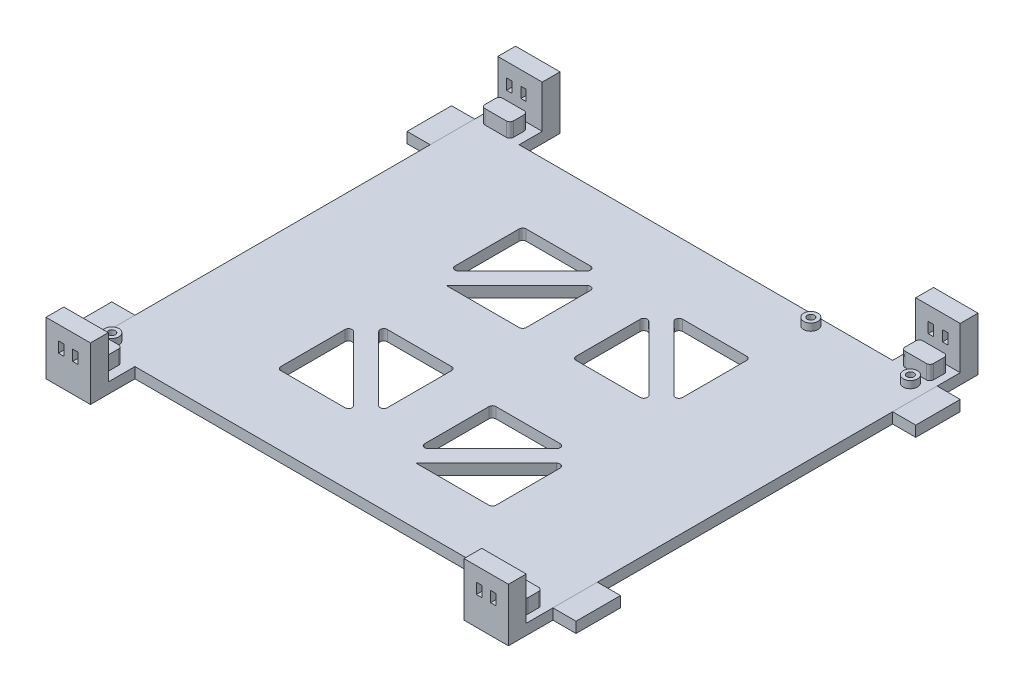
SolidWorks part; units mm, degrees
ref_plane "Front Plane" through (0, 0, 0) normal (0, 0, 1) x (1, 0, 0)
ref_plane "Top Plane" through (0, 0, 0) normal (0, 1, 0) x (1, 0, 0)
ref_plane "Right Plane" through (0, 0, 0) normal (1, 0, 0) x (0, 0, -1)
sketch "Sketch1" plane through (0, 0, 0) normal (0, 1, 0) x (1, 0, 0)
  line L0 (3, 0) -> (3, 3) construction
  line L1 (0, 0) -> (130, 0)
  line L2 (0, 0) -> (0, 108)
  line L3 (0, 108) -> (130, 108)
  line L4 (130, 0) -> (130, 108)
  line L5 (125.5, 108) -> (125.5, 105) construction
  line L6 (125.5, 105) -> (97.5, 105) construction
  line L8 (0, 0) -> (12.5, 0)
  line L9 (0, 0) -> (0, -12.5)
  line L10 (0, -12.5) -> (12.5, -12.5)
  line L11 (12.5, 0) -> (12.5, -12.5)
  line L12 (130, 0) -> (117.5, 0)
  line L13 (130, 0) -> (130, -12.5)
  line L14 (130, -12.5) -> (117.5, -12.5)
  line L15 (117.5, 0) -> (117.5, -12.5)
  line L16 (0, 108) -> (12.5, 108)
  line L17 (0, 108) -> (0, 119.5)
  line L18 (0, 119.5) -> (12.5, 119.5)
  line L19 (12.5, 108) -> (12.5, 119.5)
  line L20 (130, 108) -> (117.5, 108)
  line L21 (130, 108) -> (130, 119.5)
  line L22 (130, 119.5) -> (117.5, 119.5)
  line L23 (117.5, 108) -> (117.5, 119.5)
  circle A0 centre (3, 3) radius 1
  circle A1 centre (125.5, 105) radius 1
  circle A2 centre (97.5, 105) radius 1
  circle A3 centre (3, 3) radius 2
  circle A4 centre (97.5, 105) radius 2
  circle A5 centre (125.5, 105) radius 2
  point P7 (3, 1.5)
  point P11 (125.5, 106.5)
  dimension "D5" = 2
  dimension "D8" = 2
  dimension "D10" = 2
  dimension "D11" = 4
  dimension "D12" = 4
  dimension "D13" = 4
  dimension "D1" = 130
  dimension "D2" = 108
  dimension "D3" = 3
  dimension "D4" = 3
  dimension "D6" = 3
  dimension "D7" = 4.5
  dimension "D9" = 28
  dimension "D14" = 12.5
  dimension "D15" = 12.5
  dimension "D16" = 12.5
  dimension "D17" = 12.5
  dimension "D18" = 11.5
  dimension "D19" = 12.5
  dimension "D20" = 11.5
  dimension "D21" = 12.5
extrude "Boss-Extrude2" add sketch "Sketch1" along normal blind 3 contours L1 L4 L3 L2 A5 A4 A3 | A3 A0 | A5 A1 | A4 A2 | L3 L19 L18 L17 | L23 L3 L21 L22 | L1 L15 L14 L13 | L11 L1 L9 L10
sketch "Sketch3" plane through (0, 3, 0) normal (0, 1, 0) x (1, 0, 0)
  circle A0 centre (97.5, 105) radius 2
  circle A1 centre (125.5, 105) radius 2
  circle A2 centre (3, 3) radius 2
  circle A3 centre (3, 3) radius 1
  circle A4 centre (97.5, 105) radius 1
  circle A5 centre (125.5, 105) radius 1
  circle M7 centre (3, 3) radius 1
  circle M8 centre (97.5, 105) radius 1
  circle M9 centre (125.5, 105) radius 1
  dimension "D1" = 4
  dimension "D2" = 4
  dimension "D3" = 4
extrude "Boss-Extrude3" add sketch "Sketch3" along normal blind 2 contours A2 M7 | A0 M8 | A1 M9
sketch "Sketch5" plane through (0, 3, 0) normal (0, 1, 0) x (1, 0, 0)
  line L0 (12.5, 0) -> (12.5, -12.5) construction
  line L1 (0, -12.5) -> (12.5, -12.5)
  line L2 (0, -12.5) -> (0, -7.5)
  line L3 (0, -7.5) -> (12.5, -7.5)
  line L4 (12.5, -12.5) -> (12.5, -7.5)
  line L5 (130, -12.5) -> (130, 119.5) construction
  line L6 (117.5, -12.5) -> (130, -12.5)
  line L7 (117.5, -12.5) -> (117.5, -7.5)
  line L8 (117.5, -7.5) -> (130, -7.5)
  line L9 (130, -12.5) -> (130, -7.5)
  line L10 (12.5, 108) -> (12.5, 119.5) construction
  line L11 (0, 119.5) -> (12.5, 119.5)
  line L12 (0, 119.5) -> (0, 114.5)
  line L13 (0, 114.5) -> (12.5, 114.5)
  line L14 (12.5, 119.5) -> (12.5, 114.5)
  line L15 (117.5, 108) -> (117.5, 119.5) construction
  line L16 (130, 119.5) -> (117.5, 119.5)
  line L17 (130, 119.5) -> (130, 114.5)
  line L18 (130, 114.5) -> (117.5, 114.5)
  line L19 (117.5, 119.5) -> (117.5, 114.5)
  line M15 (117.5, 0) -> (117.5, -12.5)
  line M16 (117.5, -12.5) -> (130, -12.5)
  line M17 (130, -12.5) -> (130, 119.5)
  line M18 (130, 119.5) -> (117.5, 119.5)
  line M19 (117.5, 119.5) -> (117.5, 108)
  line M21 (12.5, 108) -> (12.5, 119.5)
  line M22 (12.5, 119.5) -> (0, 119.5)
  line M23 (0, 119.5) -> (0, -12.5)
  line M24 (0, -12.5) -> (12.5, -12.5)
  line M25 (12.5, -12.5) -> (12.5, 0)
  dimension "D1" = 5
  dimension "D2" = 5
  dimension "D3" = 5
  dimension "D4" = 5
extrude "Boss-Extrude4" add sketch "Sketch5" along normal blind 12 contours L3 M23 M24 M25 | L8 M15 M16 M17 | L13 M23 M21 M22 | L18 M17 M18 M19
sketch "Sketch6" plane through (0, 0, 12.5) normal (0, 0, 1) x (1, 0, 0)
  line L0 (6.25, 0) -> (6.25, 8) construction
  line L1 (12.5, 8) -> (0, 8) construction
  line L2 (0, 0) -> (12.5, 0) construction
  line L3 (123.75, 0) -> (123.75, 8) construction
  line L4 (130, 0) -> (117.5, 0) construction
  line L5 (0, 15) -> (0, 0) construction
  line L6 (130, 15) -> (130, 0) construction
  line L7 (130, 8) -> (117.5, 8) construction
  line L8 (3.5, 8) -> (5, 8)
  line L9 (3.5, 8) -> (3.5, 11)
  line L10 (3.5, 11) -> (5, 11)
  line L11 (5, 8) -> (5, 11)
  line L12 (7.5, 11) -> (9, 11)
  line L13 (7.5, 11) -> (7.5, 8)
  line L14 (7.5, 8) -> (9, 8)
  line L15 (9, 11) -> (9, 8)
  line L16 (121, 8) -> (122.5, 8)
  line L17 (121, 8) -> (121, 11)
  line L18 (121, 11) -> (122.5, 11)
  line L19 (122.5, 8) -> (122.5, 11)
  line L20 (125, 11) -> (126.5, 11)
  line L21 (125, 11) -> (125, 8)
  line L22 (125, 8) -> (126.5, 8)
  line L23 (126.5, 11) -> (126.5, 8)
  line L24 (117.5, 15) -> (117.5, 0) construction
  point P33 (123.75, 8)
  point P36 (6.25, 8)
  dimension "D1" = 8
  dimension "D2" = 8
  dimension "D3" = 6.25
  dimension "D4" = 6.25
  dimension "D5" = 3.5
  dimension "D6" = 3.5
  dimension "D7" = 1.5
  dimension "D8" = 3
  dimension "D9" = 0
  dimension "D10" = 2.5
  dimension "D11" = 1.5
  dimension "D12" = 3
  dimension "D13" = 0
  dimension "D14" = 0
  dimension "D16" = 2.5
  dimension "D17" = 1.5
  dimension "D18" = 3
  dimension "D19" = 1.5
  dimension "D20" = 3
extrude "Cut-Extrude1" cut sketch "Sketch6" against normal blind 5 contours L15 L12 L13 L14 | L23 L20 L21 L22 | L16 L19 L18 L17 | L9 L10 L11 L8
sketch "Sketch7" plane through (0, 0, -119.5) normal (0, 0, -1) x (-1, 0, 0)
  line L0 (-123.7456, 8) -> (-123.75, 0) construction
  line L1 (-117.4956, 8) -> (-129.9956, 8) construction
  line L2 (-6.2456, 8) -> (-6.25, 0) construction
  line L3 (0.0044, 8) -> (-12.4956, 8) construction
  line L4 (-126.5, 8) -> (-125, 8)
  line L5 (-126.5, 8) -> (-126.5, 11)
  line L6 (-126.5, 11) -> (-125, 11)
  line L7 (-125, 8) -> (-125, 11)
  line L8 (-122.5, 11) -> (-121, 11)
  line L9 (-122.5, 11) -> (-122.5, 8)
  line L10 (-122.5, 8) -> (-121, 8)
  line L11 (-121, 11) -> (-121, 8)
  line L12 (-8, 8) -> (-6.5, 8)
  line L13 (-8, 8) -> (-8, 11)
  line L14 (-8, 11) -> (-6.5, 11)
  line L15 (-6.5, 8) -> (-6.5, 11)
  line L16 (-4, 11) -> (-2.5, 11)
  line L17 (-4, 11) -> (-4, 8)
  line L18 (-4, 8) -> (-2.5, 8)
  line L19 (-2.5, 11) -> (-2.5, 8)
  line L20 (-130, 0) -> (-117.5, 0) construction
  line L21 (-130, 15) -> (-130, 0) construction
  line L22 (0, 0) -> (-12.5, 0) construction
  line L23 (0, 15) -> (0, 0) construction
  point P22 (-6.2456, 8)
  point P25 (-123.7456, 8)
  dimension "D2" = 8
  dimension "D3" = 1.5
  dimension "D4" = 3
  dimension "D5" = 2.5
  dimension "D6" = 1.5
  dimension "D7" = 3
  dimension "D8" = 0
  dimension "D9" = 0
  dimension "D10" = 0
  dimension "D11" = 2.5
  dimension "D12" = 1.5
  dimension "D13" = 3
  dimension "D14" = 1.5
  dimension "D15" = 3
  dimension "D16" = 8
  dimension "D17" = 3.5
  dimension "D18" = 2.5
extrude "Cut-Extrude2" cut sketch "Sketch7" against normal blind 5 contours L4 L7 L6 L5 | L11 L8 L9 L10 | L19 L16 L17 L18 | L12 L15 L14 L13
sketch "Sketch8" plane through (0, 3, 0) normal (0, 1, 0) x (1, 0, 0)
  line L0 (0, -7.5) -> (12.5, -7.5) construction
  line L1 (9.9039, -1) -> (1.9039, -1)
  line L2 (9.9039, -1) -> (9.9039, -6)
  line L3 (9.9039, -6) -> (1.9039, -6)
  line L4 (1.9039, -1) -> (1.9039, -6)
  line L5 (119.9954, -6) -> (127.9954, -6)
  line L6 (119.9954, -6) -> (119.9954, -1)
  line L7 (119.9954, -1) -> (127.9954, -1)
  line L8 (127.9954, -6) -> (127.9954, -1)
  line L9 (1.9039, 108) -> (9.9039, 108)
  line L10 (1.9039, 108) -> (1.9039, 113)
  line L11 (1.9039, 113) -> (9.9039, 113)
  line L12 (9.9039, 108) -> (9.9039, 113)
  line L13 (119.9954, 108) -> (127.9954, 108)
  line L14 (119.9954, 108) -> (119.9954, 113)
  line L15 (119.9954, 113) -> (127.9954, 113)
  line L16 (127.9954, 108) -> (127.9954, 113)
  line L17 (117.5, -7.5) -> (130, -7.5) construction
  line L18 (130, 114.5) -> (117.5, 114.5) construction
  line L19 (0, 114.5) -> (12.5, 114.5) construction
  dimension "D1" = 8
  dimension "D2" = 5
  dimension "D3" = 1.5
  dimension "D4" = 8
  dimension "D5" = 5
  dimension "D6" = 1.5
  dimension "D7" = 8
  dimension "D8" = 5
  dimension "D9" = 1.5
  dimension "D10" = 5
  dimension "D11" = 8
  dimension "D12" = 1.5
extrude "Boss-Extrude5" add sketch "Sketch8" along normal blind 4 contours L9 L12 L11 L10 | L13 L16 L15 L14 | L5 L8 L7 L6 | L1 L4 L3 L2
sketch "Sketch9" plane through (0, 3, 0) normal (0, 1, 0) x (1, 0, 0)
  line L0 (12.5, 108) -> (0, 108) construction
  line L1 (0, -7.5) -> (0, 114.5) construction
  line L2 (12.5, 0) -> (0, 0) construction
  line L3 (117.5, 0) -> (130, 0) construction
  line L4 (130, -7.5) -> (130, 114.5) construction
  line L5 (117.5, 108) -> (130, 108) construction
  line L7 (0, 0) -> (-6.5, 0)
  line L8 (0, 0) -> (0, 12.5)
  line L9 (0, 12.5) -> (-6.5, 12.5)
  line L10 (-6.5, 0) -> (-6.5, 12.5)
  line L11 (0, 108) -> (-6.5, 108)
  line L12 (0, 108) -> (0, 95.5)
  line L13 (0, 95.5) -> (-6.5, 95.5)
  line L14 (-6.5, 108) -> (-6.5, 95.5)
  line L15 (130, 0) -> (136.5, 0)
  line L16 (130, 0) -> (130, 12.5)
  line L17 (130, 12.5) -> (136.5, 12.5)
  line L18 (136.5, 0) -> (136.5, 12.5)
  line L19 (130, 108) -> (136.5, 108)
  line L20 (130, 108) -> (130, 95.5)
  line L21 (130, 95.5) -> (136.5, 95.5)
  line L22 (136.5, 108) -> (136.5, 95.5)
  line M14 (0, 114.5) -> (0, -7.5)
  line M20 (130, -7.5) -> (130, 114.5)
  dimension "D1" = 6.5
  dimension "D2" = 12.5
  dimension "D3" = 6.5
  dimension "D4" = 12.5
  dimension "D5" = 6.5
  dimension "D6" = 12.5
  dimension "D7" = 6.5
  dimension "D8" = 12.5
extrude "Boss-Extrude6" add sketch "Sketch9" against normal blind 3 separate body contours L15 L18 L17 M20 | L22 L19 L21 M20 | L10 L7 L9 M14 | L11 L14 L13 M14
sketch "Sketch10" plane through (0, 3, 0) normal (0, 1, 0) x (1, 0, 0)
  line L0 (0, 12.5) -> (130, 12.5) construction
  line L1 (0, 95.5) -> (130, 95.5) construction
  line L2 (65, 0) -> (65, 108) construction
  line L3 (12.5, 0) -> (117.5, 0) construction
  line L4 (12.5, 108) -> (117.5, 108) construction
  line L5 (39.944, 51.444) -> (26.056, 37.556) construction
  line L6 (72, 16) -> (97, 16)
  line L7 (72, 16) -> (72, 41)
  line L8 (72, 41) -> (97, 41)
  line L9 (97, 16) -> (97, 41)
  line L10 (72, 88.5) -> (97, 88.5)
  line L11 (72, 88.5) -> (72, 63.5)
  line L12 (72, 63.5) -> (97, 63.5)
  line L13 (97, 88.5) -> (97, 63.5)
  line L14 (58, 19.5) -> (33, 19.5)
  line L15 (58, 19.5) -> (58, 44.5)
  line L16 (58, 44.5) -> (33, 44.5)
  line L17 (33, 19.5) -> (33, 44.5)
  line L18 (58, 88.5) -> (33, 88.5)
  line L19 (58, 88.5) -> (58, 63.5)
  line L20 (58, 63.5) -> (33, 63.5)
  line L21 (33, 88.5) -> (33, 63.5)
  line L22 (31.2322, 42.7322) -> (34.7678, 46.2678)
  line L23 (31.2322, 42.7322) -> (60.1842, 13.7803)
  line L24 (34.7678, 46.2678) -> (63.7197, 17.3158)
  line L25 (60.1842, 13.7803) -> (63.7197, 17.3158)
  line L26 (28.3046, 68.1954) -> (37.6954, 58.8046) construction
  line L27 (34.7678, 61.7322) -> (31.2322, 65.2678)
  line L28 (34.7678, 61.7322) -> (62.8704, 89.8349)
  line L29 (31.2322, 65.2678) -> (59.3349, 93.3704)
  line L30 (62.8704, 89.8349) -> (59.3349, 93.3704)
  line L31 (67.2828, 20.7172) -> (76.7172, 11.2828) construction
  line L32 (73.7678, 14.2322) -> (70.2322, 17.7678)
  line L33 (73.7678, 14.2322) -> (104.6691, 45.1336)
  line L34 (70.2322, 17.7678) -> (101.1336, 48.6691)
  line L35 (104.6691, 45.1336) -> (101.1336, 48.6691)
  line L36 (91.7204, 58.2204) -> (102.2796, 68.7796) construction
  line L37 (95.2322, 61.7322) -> (98.7678, 65.2678)
  line L38 (95.2322, 61.7322) -> (67.9584, 89.0061)
  line L39 (98.7678, 65.2678) -> (71.4939, 92.5416)
  line L40 (67.9584, 89.0061) -> (71.4939, 92.5416)
  point P33 (33, 44.5)
  point P40 (33, 63.5)
  point P47 (72, 16)
  point P54 (97, 63.5)
  dimension "D1" = 7
  dimension "D2" = 7
  dimension "D3" = 25
  dimension "D4" = 25
  dimension "D5" = 7
  dimension "D6" = 7
  dimension "D7" = 25
  dimension "D8" = 25
  dimension "D9" = 7
  dimension "D10" = 7
  dimension "D11" = 25
  dimension "D12" = 25
  dimension "D13" = 7
  dimension "D14" = 7
  dimension "D15" = 25
  dimension "D16" = 25
  dimension "D17" = 5
  dimension "D18" = 2.5
  dimension "D19" = 2.5
  dimension "D20" = 5
  dimension "D21" = 2.5
  dimension "D22" = 5
  dimension "D23" = 2.5
  dimension "D24" = 5
extrude "Cut-Extrude3" cut sketch "Sketch10" against normal blind 3 contours L33 L6 L9 | L7 L34 L8 | L12 L38 L11 | L39 L13 L10 | L16 L24 L15 | L28 L20 L19 | L21 L29 L18 | L23 L17 L14
fillet "Fillet1" radius 1 38 edges at (75.5355, 1.5, -88.5) (36.5355, 1.5, -44.5) (97, 1.5, -37.4645) (58, 1.5, -84.9645) (93.4645, 1.5, -41) (54.4645, 1.5, -88.5) (33, 1.5, -67.0355) (72, 1.5, -19.5355) (33, 1.5, -40.9645) (72, 1.5, -84.9645) (54.4645, 1.5, -19.5) (93.4645, 1.5, -63.5) (58, 1.5, -63.5) (97, 1.5, -16) (72, 1.5, -63.5) (33, 1.5, -19.5) (72, 1.5, -41) (33, 1.5, -88.5) (58, 1.5, -44.5) (97, 1.5, -88.5) (58, 1.5, -23.0355) (97, 1.5, -67.0355) (119.9954, 5, -113) (1.9039, 5, -113) (9.9039, 5, -113) (127.9954, 5, -113) (9.9039, 5, -108) (127.9954, 5, -108) (127.9954, 5, 6) (9.9039, 5, 6) (1.9039, 5, -108) (119.9954, 5, -108) (119.9954, 5, 6) (1.9039, 5, 6) (9.9039, 5, 1) (1.9039, 5, 1) (127.9954, 5, 1) (119.9954, 5, 1)
